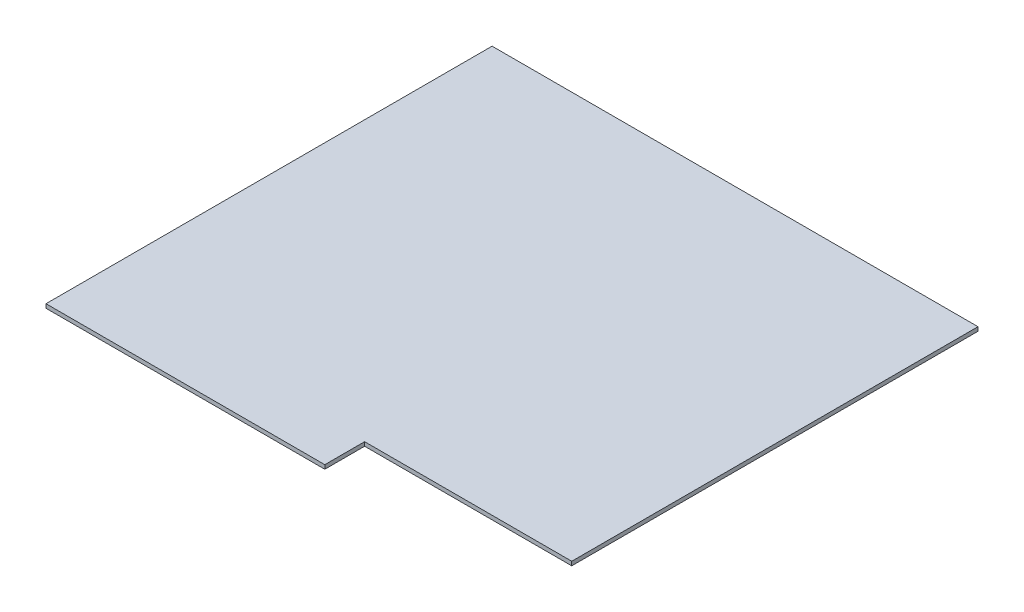
SolidWorks part; units mm, degrees
ref_plane "Front Plane" through (0, 0, 0) normal (0, 0, 1) x (1, 0, 0)
ref_plane "Top Plane" through (0, 0, 0) normal (0, 1, 0) x (1, 0, 0)
ref_plane "Right Plane" through (0, 0, 0) normal (1, 0, 0) x (0, 0, -1)
sketch "Sketch1" plane through (0, 0, 0) normal (0, 1, 0) x (1, 0, 0)
  line L0 (521.3431, -2869.08) -> (-2978.6569, -2869.08)
  line L1 (3121.3431, -2369.08) -> (3121.3431, 2730.92)
  line L2 (3121.3431, 2730.92) -> (-2978.6569, 2730.92)
  line L3 (-2978.6569, -2869.08) -> (-2978.6569, 2730.92)
  line L4 (2671.0308, -2455.6785) -> (-2978.6569, 2730.92) construction
  line L5 (3121.3431, 2730.92) -> (-2978.6569, -2869.08) construction
  line L6 (3121.3431, -2369.08) -> (521.3431, -2369.08)
  line L7 (521.3431, -2369.08) -> (521.3431, -2869.08)
  line L8 (3121.3431, -2369.08) -> (521.3431, -2869.08) construction
  line L9 (1753.5664, -2632.114) -> (521.3431, -2369.08) construction
  point P0 (71.3431, -69.08)
  point P7 (1753.5664, -2632.114)
  dimension "D1" = 5600
  dimension "D2" = 6100
  dimension "D3" = 500
  dimension "D4" = 2600
extrude "Boss-Extrude1" add sketch "Sketch1" along normal blind 50
sketch "Sketch2" plane through (0, 0, 0) normal (0, -1, 0) x (1, 0, 0)
  line L0 (-1828.6569, -180.92) -> (-1078.6569, -180.92) construction
  line L1 (71.3431, -2730.92) -> (71.3431, 2869.08) construction
  line L3 (-1828.6569, -555.92) -> (-1078.6569, -555.92)
  line L4 (-2978.6569, -2730.92) -> (-2978.6569, 2869.08) construction
  line L5 (-1828.6569, -555.92) -> (-1828.6569, 194.08)
  line L6 (3121.3431, -2730.92) -> (-2978.6569, -2730.92) construction
  line L7 (-2978.6569, 2869.08) -> (521.3431, 2869.08) construction
  line L8 (-1453.6569, 2869.08) -> (-1453.6569, -2730.92) construction
  line L9 (1596.3431, -2730.92) -> (1596.3431, 2369.08) construction
  line L14 (-1828.6569, 194.08) -> (-1078.6569, 194.08)
  line L15 (-1078.6569, -555.92) -> (-1078.6569, 194.08)
  line L16 (521.3431, 2369.08) -> (3121.3431, 2369.08) construction
  line L17 (1221.3431, -180.92) -> (1971.3431, -180.92) construction
  line L18 (1971.3431, -555.92) -> (1221.3431, -555.92)
  line L19 (1971.3431, -555.92) -> (1971.3431, 194.08)
  line L20 (1971.3431, 194.08) -> (1221.3431, 194.08)
  line L21 (1221.3431, -555.92) -> (1221.3431, 194.08)
  line L22 (1971.3431, -555.92) -> (1221.3431, 194.08) construction
  line L23 (1971.3431, 194.08) -> (1221.3431, -555.92) construction
  line L24 (3121.3431, -180.92) -> (-2978.6569, -180.92) construction
  line L25 (3121.3431, 2369.08) -> (3121.3431, -2730.92) construction
  line L26 (-1828.6569, -555.92) -> (-1078.6569, 194.08) construction
  line L27 (-1828.6569, 194.08) -> (-1078.6569, -555.92) construction
  point P15 (-1453.6569, 69.08)
  point P16 (-1453.6569, -180.92)
  point P24 (1596.3431, -180.92)
  dimension "D1" = 3050
  dimension "D2" = 1525
  dimension "D3" = 750
  dimension "D4" = 750
  dimension "D5" = 1525
  dimension "D6" = 750
  dimension "D7" = 750
extrude "Cut-Extrude1" cut sketch "Sketch2" against normal blind 10
